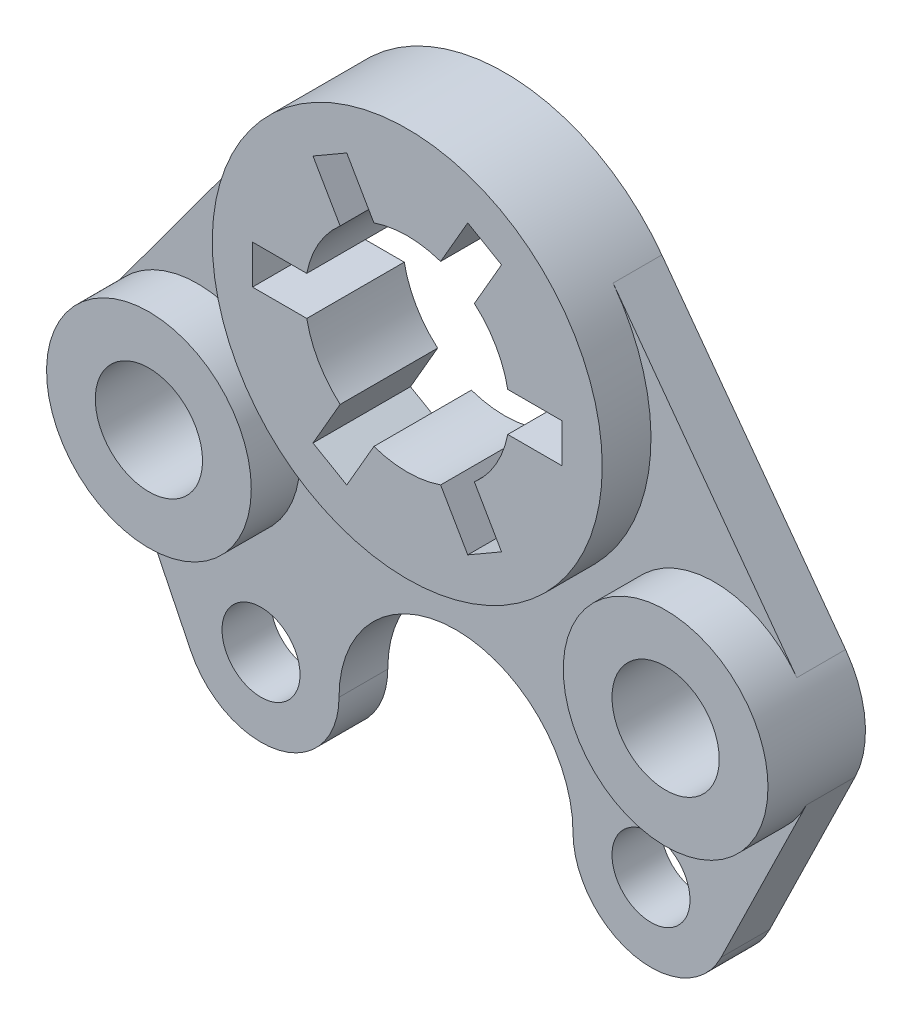
SolidWorks part; units mm, degrees
ref_plane "Alzado" through (0, 0, 0) normal (0, 0, 1) x (1, 0, 0)
ref_plane "Planta" through (0, 0, 0) normal (0, 1, 0) x (1, 0, 0)
ref_plane "Vista lateral" through (0, 0, 0) normal (1, 0, 0) x (0, 0, -1)
sketch "Croquis1" plane through (0, 0, 0) normal (0, 0, 1) x (1, 0, 0)
  line L0 (0, 74.4598) -> (0, -96.2842) construction
  line L1 (-32.2246, 23.6976) -> (-69.9179, -27.5588)
  line L2 (-71.8686, -49.2182) -> (-54.3761, -85.0234)
  line L3 (71.8686, -49.2182) -> (54.3761, -85.0234)
  line L4 (32.2246, 23.6976) -> (69.9179, -27.5588)
  arc A0 (32.2246, 23.6976) -> (-32.2246, 23.6976) centre (0, 0) ccw
  arc A1 (-69.9179, -27.5588) -> (-71.8686, -49.2182) centre (-53, -40) ccw
  arc A2 (-54.3761, -85.0234) -> (-24, -78) centre (-40, -78) ccw
  arc A3 (54.3761, -85.0234) -> (24, -78) centre (40, -78) cw
  arc A4 (69.9179, -27.5588) -> (71.8686, -49.2182) centre (53, -40) cw
  arc A5 (-24, -78) -> (24, -78) centre (0, -78) cw
  circle A6 centre (-40, -78) radius 8
  circle A7 centre (40, -78) radius 8
  dimension "D1" = 80
  dimension "D6" = 42
  dimension "D7" = 24
  dimension "D8" = 16
  dimension "D9" = 16
  dimension "D2" = 40
  dimension "D3" = 38
  dimension "D4" = 80
  dimension "D5" = 106
extrude "Saliente-Extruir1" add sketch "Croquis1" along normal blind 10
sketch "Croquis2" plane through (0, 0, 10) normal (0, 0, 1) x (1, 0, 0)
  line L4 (-32.2246, 23.6976) -> (-69.9179, -27.5588)
  line L5 (-71.8686, -49.2182) -> (-54.3761, -85.0234)
  line L6 (54.3761, -85.0234) -> (71.8686, -49.2182)
  line L7 (69.9179, -27.5588) -> (32.2246, 23.6976)
  line L8 (-32.2246, 23.6976) -> (-69.9179, -27.5588)
  line L9 (-71.8686, -49.2182) -> (-54.3761, -85.0234)
  line L10 (54.3761, -85.0234) -> (71.8686, -49.2182)
  line L11 (69.9179, -27.5588) -> (32.2246, 23.6976)
  circle A0 centre (-53, -40) radius 21
  circle A1 centre (53, -40) radius 21
  circle A2 centre (0, 0) radius 40
  arc A6 (32.2246, 23.6976) -> (-32.2246, 23.6976) centre (0, 0) ccw
  arc A7 (-69.9179, -27.5588) -> (-71.8686, -49.2182) centre (-53, -40) ccw
  arc A8 (-54.3761, -85.0234) -> (-24, -78) centre (-40, -78) ccw
  arc A9 (24, -78) -> (-24, -78) centre (0, -78) ccw
  arc A10 (24, -78) -> (54.3761, -85.0234) centre (40, -78) ccw
  arc A11 (71.8686, -49.2182) -> (69.9179, -27.5588) centre (53, -40) ccw
  arc A12 (32.2246, 23.6976) -> (-32.2246, 23.6976) centre (0, 0) ccw
  arc A13 (-69.9179, -27.5588) -> (-71.8686, -49.2182) centre (-53, -40) ccw
  arc A14 (-54.3761, -85.0234) -> (-24, -78) centre (-40, -78) ccw
  arc A15 (24, -78) -> (-24, -78) centre (0, -78) ccw
  arc A16 (24, -78) -> (54.3761, -85.0234) centre (40, -78) ccw
  arc A17 (71.8686, -49.2182) -> (69.9179, -27.5588) centre (53, -40) ccw
  arc M12 (32.2246, 23.6976) -> (-32.2246, 23.6976) centre (0, 0) ccw
  arc M14 (-69.9179, -27.5588) -> (-71.8686, -49.2182) centre (-53, -40) ccw
  arc M20 (71.8686, -49.2182) -> (69.9179, -27.5588) centre (53, -40) ccw
  dimension "D1" = 0
extrude "Saliente-Extruir2" add sketch "Croquis2" along normal blind 10 contours A2 M12 | A0 M14 | A1 M20
sketch "Croquis3" plane through (0, 0, 20) normal (0, 0, 1) x (1, 0, 0)
  line L0 (-31.749, 4) -> (-31.749, -4)
  line L1 (-31.749, 4) -> (-20.6155, 4)
  line L2 (-31.749, -4) -> (-20.6155, -4)
  line L3 (-12.4104, 29.4955) -> (-6.8437, 19.8536)
  line L4 (54.3761, -85.0234) -> (71.8686, -49.2182)
  line L5 (69.9179, -27.5588) -> (32.2246, 23.6976)
  line L6 (-32.2246, 23.6976) -> (-69.9179, -27.5588)
  line L7 (-71.8686, -49.2182) -> (-54.3761, -85.0234)
  line L8 (54.3761, -85.0234) -> (71.8686, -49.2182)
  line L9 (69.9179, -27.5588) -> (32.2246, 23.6976)
  line L10 (-32.2246, 23.6976) -> (-69.9179, -27.5588)
  line L11 (-71.8686, -49.2182) -> (-54.3761, -85.0234)
  line L12 (-12.4104, 29.4955) -> (-19.3386, 25.4955)
  line L13 (-19.3386, 25.4955) -> (-13.7719, 15.8536)
  line L14 (19.3386, 25.4955) -> (13.7719, 15.8536)
  line L15 (19.3386, 25.4955) -> (12.4104, 29.4955)
  line L16 (12.4104, 29.4955) -> (6.8437, 19.8536)
  line L17 (31.749, -4) -> (20.6155, -4)
  line L18 (31.749, -4) -> (31.749, 4)
  line L19 (31.749, 4) -> (20.6155, 4)
  line L20 (12.4104, -29.4955) -> (6.8437, -19.8536)
  line L21 (12.4104, -29.4955) -> (19.3386, -25.4955)
  line L22 (19.3386, -25.4955) -> (13.7719, -15.8536)
  line L23 (-19.3386, -25.4955) -> (-13.7719, -15.8536)
  line L24 (-19.3386, -25.4955) -> (-12.4104, -29.4955)
  line L25 (-12.4104, -29.4955) -> (-6.8437, -19.8536)
  circle A0 centre (0, 0) radius 40 construction
  circle A1 centre (-53, -40) radius 21 construction
  circle A2 centre (53, -40) radius 21 construction
  circle A3 centre (0, 0) radius 40
  circle A4 centre (-53, -40) radius 21
  circle A5 centre (53, -40) radius 21
  circle A6 centre (-53, -40) radius 11
  circle A7 centre (0, 0) radius 32 construction
  arc A8 (-20.6155, -4) -> (-13.7719, -15.8536) centre (0, 0) ccw
  circle A9 centre (53, -40) radius 11
  arc A10 (-13.7719, 15.8536) -> (-20.6155, 4) centre (0, 0) ccw
  arc A11 (6.8437, 19.8536) -> (-6.8437, 19.8536) centre (0, 0) ccw
  arc A12 (69.9179, -27.5588) -> (71.8686, -49.2182) centre (53, -40) ccw
  arc A13 (-32.2246, 23.6976) -> (32.2246, 23.6976) centre (0, 0) ccw
  arc A14 (-71.8686, -49.2182) -> (-69.9179, -27.5588) centre (-53, -40) ccw
  arc A15 (-54.3761, -85.0234) -> (-24, -78) centre (-40, -78) ccw
  arc A16 (24, -78) -> (-24, -78) centre (0, -78) ccw
  arc A17 (24, -78) -> (54.3761, -85.0234) centre (40, -78) ccw
  arc A18 (69.9179, -27.5588) -> (71.8686, -49.2182) centre (53, -40) ccw
  arc A19 (-32.2246, 23.6976) -> (32.2246, 23.6976) centre (0, 0) ccw
  arc A20 (-71.8686, -49.2182) -> (-69.9179, -27.5588) centre (-53, -40) ccw
  arc A21 (-54.3761, -85.0234) -> (-24, -78) centre (-40, -78) ccw
  arc A22 (24, -78) -> (-24, -78) centre (0, -78) ccw
  arc A23 (24, -78) -> (54.3761, -85.0234) centre (40, -78) ccw
  arc A24 (20.6155, 4) -> (13.7719, 15.8536) centre (0, 0) ccw
  arc A25 (13.7719, -15.8536) -> (20.6155, -4) centre (0, 0) ccw
  arc A26 (-6.8437, -19.8536) -> (6.8437, -19.8536) centre (0, 0) ccw
  point P55 (0, 0)
  dimension "D2" = 22
  dimension "D3" = 64
  dimension "D4" = 42
  dimension "D5" = 8
  dimension "D1" = 0
  dimension "D6" = 6
extrude "Cortar-Extruir1" cut sketch "Croquis3" against normal through all contours L25 A26 L20 L21 L22 A25 L17 L18 L19 A24 L14 L15 L16 A11 L3 L12 L13 A10 L1 L0 L2 A8 L23 L24 | A9 | A6
